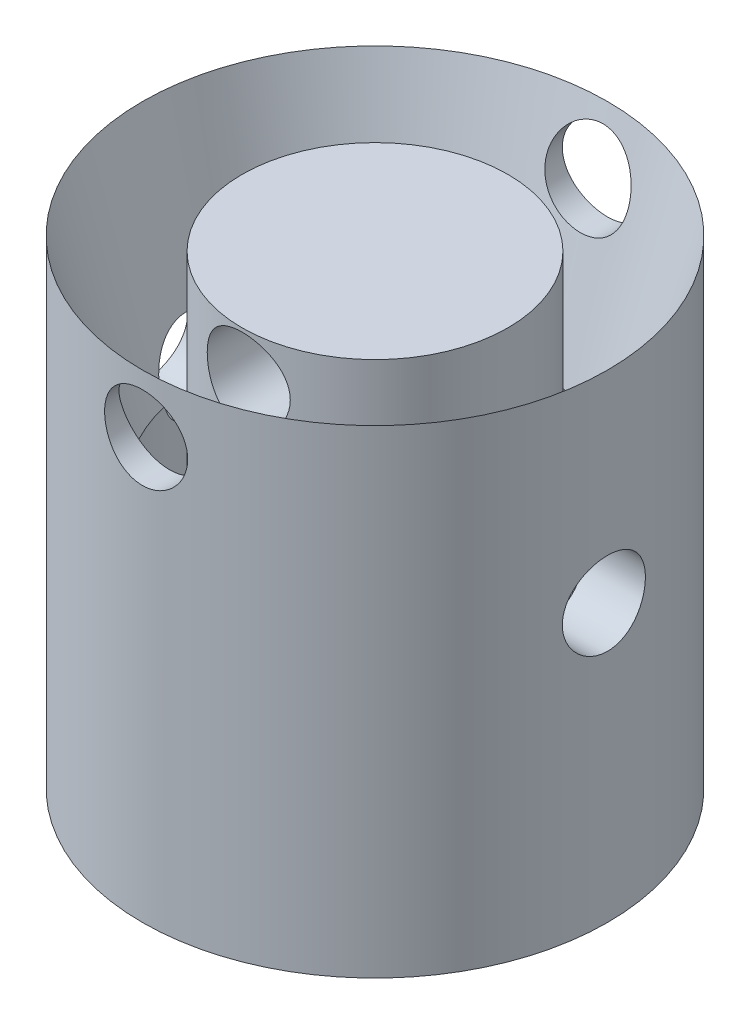
SolidWorks part; units mm, degrees
ref_plane "Front Plane" through (0, 0, 0) normal (1, 0, 0) x (0, 1, 0)
ref_plane "Top Plane" through (0, 0, 0) normal (0, 0, 1) x (0, 1, 0)
ref_plane "Right Plane" through (0, 0, 0) normal (0, 1, 0) x (-1, 0, 0)
sketch "Sketch1" plane through (0, 0, 0) normal (1, 0, 0) x (0, 1, 0)
  line L0 (0, 0) -> (44.45, 0)
  line L1 (44.45, 0) -> (44.45, 12.7)
  line L2 (44.45, 12.7) -> (12.7, 12.7)
  line L3 (12.7, 12.7) -> (12.7, 16.7005)
  line L4 (12.7, 16.7005) -> (25.4, 16.7005)
  line L5 (25.4, 16.7005) -> (45.72, 22.225)
  line L6 (45.72, 22.225) -> (0, 22.225)
  line L7 (0, 22.225) -> (0, 0)
  dimension "D1" = 44.45
  dimension "D2" = 12.7
  dimension "D3" = 12.7
  dimension "D4" = 12.7
  dimension "D5" = 16.7005
  dimension "D6" = 33.02
  dimension "D7" = 22.225
revolve "Revolve1" add sketch "Sketch1" angle 360 about L0
sketch "Sketch2" plane through (0, 0, 0) normal (0, 0, 1) x (0, 1, 0)
  line L0 (45.72, -22.225) -> (45.72, 22.225) construction
  line L1 (0, 0) -> (45.72, 0) construction
  line L2 (45.72, 0) -> (53.848, 0) construction
  line L3 (53.848, 0) -> (40.132, 0) construction
  line L4 (40.132, 0) -> (26.416, 0) construction
  line L5 (26.416, 0) -> (12.7, 0) construction
  circle A1 centre (40.132, 0) radius 3.9687
  point P0 (45.72, 0)
  point P1 (-3.4062, 6.1377)
  point P4 (0, 0)
  point P8 (40.132, 0)
  point P9 (26.416, 0)
  dimension "D3" = 7.9375
  dimension "D1" = 8.128
  dimension "D2" = 12.7
extrude "Cut-Extrude1" cut sketch "Sketch2" against normal through all both and the other way through all contours A1
sketch "Sketch4" plane through (0, 0, 0) normal (1, 0, 0) x (0, 1, 0)
  circle A0 centre (26.416, 0) radius 3.9688
  point P0 (26.416, 0)
  dimension "D1" = 7.9375
extrude "Cut-Extrude2" cut sketch "Sketch4" against normal through all both and the other way through all
